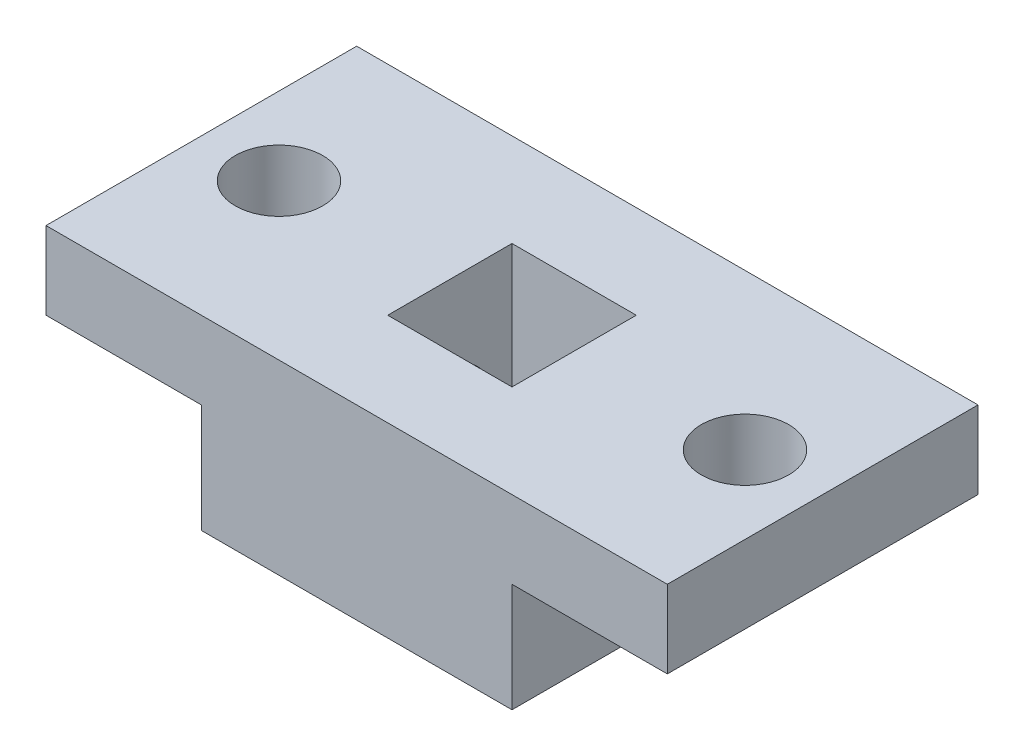
SolidWorks part; units mm, degrees
ref_plane "Front Plane" through (0, 0, 0) normal (0, 0, 1) x (1, 0, 0)
ref_plane "Top Plane" through (0, 0, 0) normal (0, 1, 0) x (1, 0, 0)
ref_plane "Right Plane" through (0, 0, 0) normal (1, 0, 0) x (0, 0, -1)
sketch "Sketch1" plane through (0, 0, 0) normal (0, 0, 1) x (1, 0, 0)
  line L0 (0, 0) -> (0, 7.62)
  line L1 (0, 7.62) -> (12.7, 7.62)
  line L2 (12.7, 7.62) -> (12.7, 4.445)
  line L3 (12.7, 4.445) -> (6.35, 4.445)
  line L4 (6.35, 4.445) -> (6.35, 0)
  line L5 (6.35, 0) -> (0, 0)
  dimension "D1" = 12.7
  dimension "D2" = 7.62
  dimension "D3" = 3.175
  dimension "D4" = 6.35
extrude "Boss-Extrude1" add sketch "Sketch1" along normal blind 12.7 contours L0 L1 L2 L3 L4 L5
mirror "Mirror1" about plane through (0, 0, 12.7) normal (-1, 0, 0) of bodies 101
sketch "Sketch2" plane through (-6.35, 0, 0) normal (-1, 0, 0) x (0, 0, 1)
  line L1 (6.35, 2.8575) -> (0, 0) construction
  line L2 (6.35, 2.8575) -> (12.7, 0) construction
  line L5 (12.7, 4.445) -> (0, 4.445) construction
  circle A0 centre (6.35, 2.8575) radius 1.5875
  dimension "D1" = 3.175
sketch "Sketch3" plane through (0, 7.62, 0) normal (0, 1, 0) x (1, 0, 0)
  line L0 (-2.54, -3.81) -> (-12.7, 0) construction
  line L1 (-12.7, -12.7) -> (-12.7, 0) construction
  line L2 (2.54, -3.81) -> (12.7, 0) construction
  line L3 (-12.7, 0) -> (12.7, 0) construction
  line L4 (-2.54, -8.89) -> (-12.7, -12.7) construction
  line L20 (-2.54, -3.81) -> (-2.54, -8.89)
  line L21 (2.54, -3.81) -> (-2.54, -3.81)
  line L22 (2.54, -8.89) -> (2.54, -3.81)
  line L23 (-2.54, -8.89) -> (2.54, -8.89)
  dimension "D1" = 5.08
  dimension "D3" = 5.08
extrude "Cut-Extrude1" cut sketch "Sketch3" against normal offset from surface (6.35 mm away) 1.27 up to face at (0, 0, 6.35)
extrude "Cut-Extrude2" cut sketch "Sketch2" against normal up to surface (3.81 mm away) up to face at (-2.54, 4.445, 6.35)
sketch "Sketch4" plane through (0, 4.445, 0) normal (0, -1, 0) x (1, 0, 0)
  line L0 (9.525, 6.35) -> (-9.525, 6.35) construction
  line L1 (9.525, 6.35) -> (12.7, 6.35) construction
  line L2 (-9.525, 6.35) -> (-12.7, 6.35) construction
  line L3 (9.525, 6.35) -> (12.7, 0) construction
  line L4 (-12.7, 12.7) -> (-12.7, 0) construction
  line L5 (12.7, 12.7) -> (12.7, 0) construction
  line L7 (9.525, 6.35) -> (12.7, 12.7) construction
  line L8 (-12.7, 12.7) -> (12.7, 12.7) construction
  circle A0 centre (9.525, 6.35) radius 1.7859
  circle A1 centre (-9.525, 6.35) radius 1.7859
  dimension "D1" = 3.5719
  dimension "D2" = 3.5719
  dimension "D4" = 3.175
extrude "Cut-Extrude3" cut sketch "Sketch4" against normal up to next
mirror "Mirror2" [suppressed]
